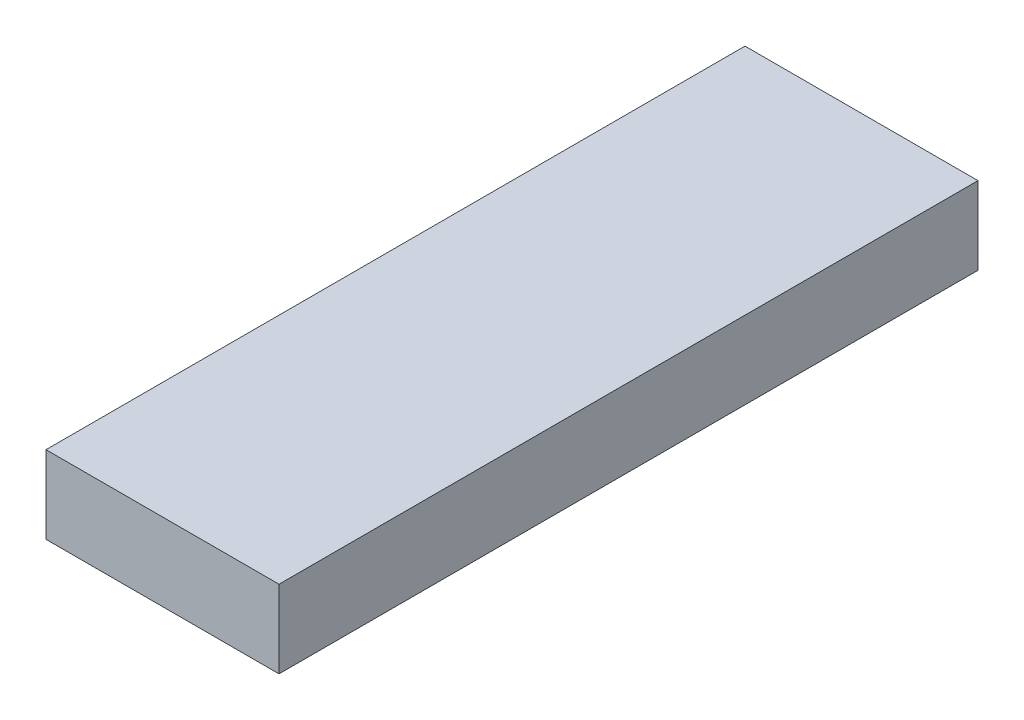
SolidWorks part; units mm, degrees
ref_plane "Front Plane" through (0, 0, 0) normal (0, 0, 1) x (1, 0, 0)
ref_plane "Top Plane" through (0, 0, 0) normal (0, 1, 0) x (1, 0, 0)
ref_plane "Right Plane" through (0, 0, 0) normal (1, 0, 0) x (0, 0, -1)
sketch "Sketch1" plane through (0, 0, 0) normal (0, 1, 0) x (1, 0, 0)
  line L1 (-1500, -4500) -> (1500, -4500)
  line L2 (-1500, -4500) -> (-1500, 4500)
  line L3 (-1500, 4500) -> (1500, 4500)
  line L4 (1500, -4500) -> (1500, 4500)
  line L5 (-1500, -4500) -> (1500, 4500) construction
  line L6 (-1500, 4500) -> (1500, -4500) construction
  point P0 (0, 0)
  dimension "D1" = 3000
  dimension "D2" = 9000
extrude "Boss-Extrude1" add sketch "Sketch1" along normal blind 1000
